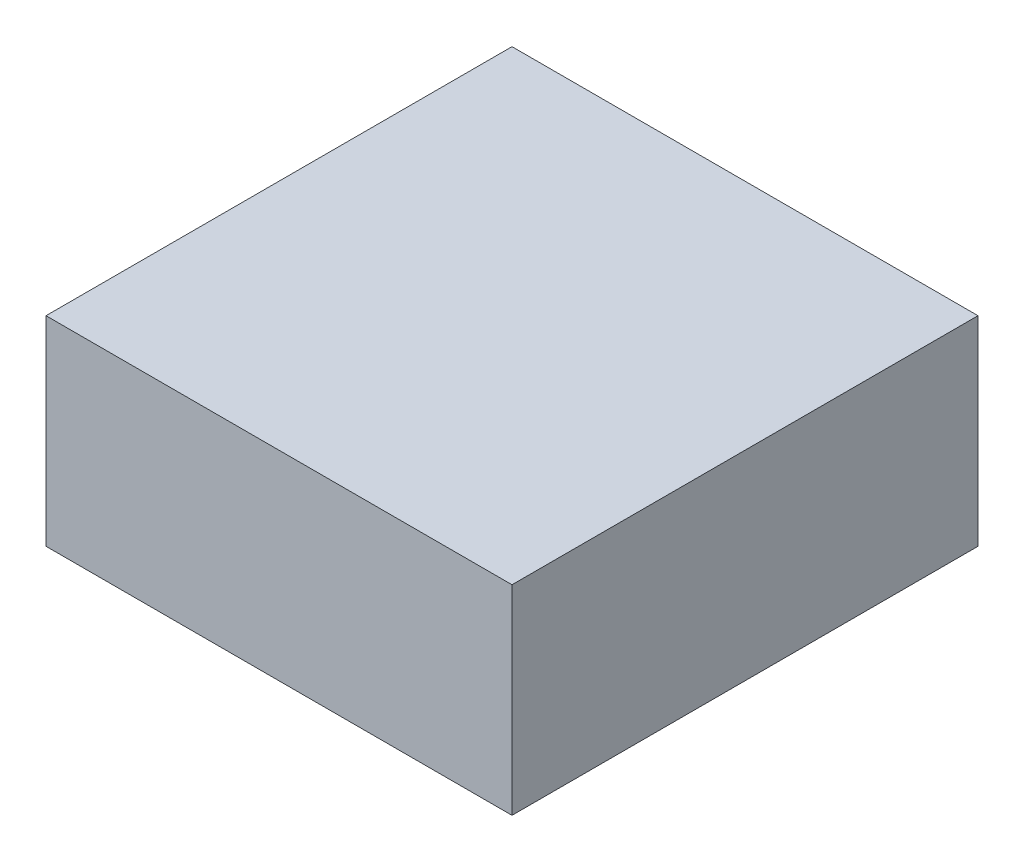
SolidWorks part; units mm, degrees
ref_plane "Front Plane" through (0, 0, 0) normal (0, 0, 1) x (1, 0, 0)
ref_plane "Top Plane" through (0, 0, 0) normal (0, 1, 0) x (1, 0, 0)
ref_plane "Right Plane" through (0, 0, 0) normal (1, 0, 0) x (0, 0, -1)
sketch "Sketch1" plane through (0, 0, 0) normal (0, 0, 1) x (1, 0, 0)
  line L1 (0, 0) -> (177.8, 0)
  line L2 (0, 0) -> (0, 76.2)
  line L3 (0, 76.2) -> (177.8, 76.2)
  line L4 (177.8, 0) -> (177.8, 76.2)
  dimension "D1" = 76.2
  dimension "D2" = 177.8
extrude "Boss-Extrude1" add sketch "Sketch1" along normal blind 177.8
